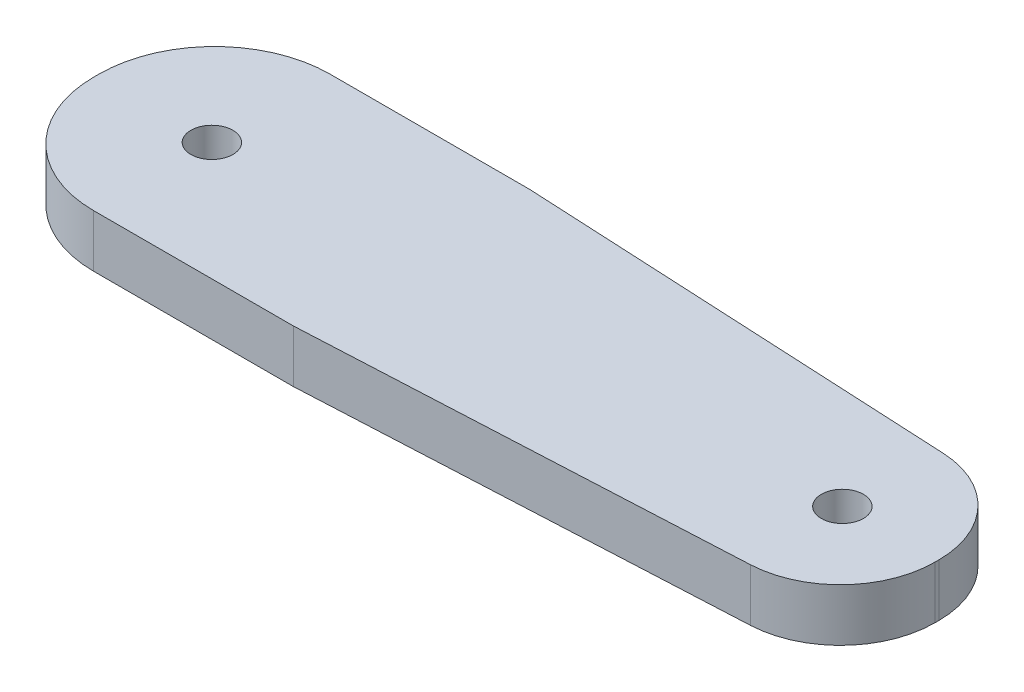
SolidWorks part; units mm, degrees
ref_plane "Front Plane" through (0, 0, 0) normal (0, 0, 1) x (1, 0, 0)
ref_plane "Top Plane" through (0, 0, 0) normal (0, 1, 0) x (1, 0, 0)
ref_plane "Right Plane" through (0, 0, 0) normal (1, 0, 0) x (0, 0, -1)
sketch "Sketch1" plane through (0, 0, 0) normal (0, 1, 0) x (1, 0, 0)
  line L1 (-95, 22.5) -> (95, 22.5)
  line L2 (-95, 22.5) -> (-95, -22.5)
  line L3 (-95, -22.5) -> (95, -22.5)
  line L4 (95, 22.5) -> (95, -22.5)
  line L5 (-95, 22.5) -> (95, -22.5) construction
  line L6 (-95, -22.5) -> (95, 22.5) construction
  point P0 (0, 0)
  dimension "D1" = 45
  dimension "D2" = 190
extrude "Boss-Extrude1" add sketch "Sketch1" along normal blind 10
sketch "Sketch2" plane through (0, 10, 0) normal (0, 1, 0) x (1, 0, 0)
  line L0 (-95, 0) -> (-75, 0) construction
  line L1 (-95, 22.5) -> (-95, -22.5) construction
  line L2 (-75, 0) -> (-43, 0) construction
  line L10 (-43, 0) -> (77, 0) construction
  circle A5 centre (-43, 0) radius 4
  circle A8 centre (77, 0) radius 4
  dimension "D9" = 8
  dimension "D13" = 8
  dimension "D2" = 20
  dimension "D8" = 32
  dimension "D12" = 120
extrude "Cut-Extrude1" cut sketch "Sketch2" against normal blind 10
sketch "Sketch3" plane through (0, 10, 0) normal (0, 1, 0) x (1, 0, 0)
  line L0 (95, -22.5) -> (-5, -22.5)
  line L1 (-95, -22.5) -> (95, -22.5) construction
  line L2 (95, -22.5) -> (95, -17.5)
  line L3 (95, -22.5) -> (95, 22.5) construction
  line L4 (-5, -22.5) -> (95, -17.5)
  line L5 (-5.5, 0) -> (5.5, 0) construction
  line L6 (-5, 22.5) -> (95, 17.5)
  line L7 (95, 22.5) -> (95, 17.5)
  line L8 (95, 22.5) -> (-5, 22.5)
  line L10 (-95, 22.5) -> (-65, 22.5)
  line L11 (-95, 22.5) -> (-95, -22.5)
  line L12 (-95, -22.5) -> (-65, -22.5)
  line L13 (-65, 22.5) -> (-65, -22.5)
  dimension "D1" = 100
  dimension "D2" = 5
  dimension "D3" = 30
extrude "Cut-Extrude2" cut sketch "Sketch3" against normal blind 10
fillet "Fillet1" radius 18 2 edges at (95, 5, -17.5) (95, 5, 17.5)
fillet "Fillet2" radius 22 2 edges at (-65, 5, -22.5) (-65, 5, 22.5)
